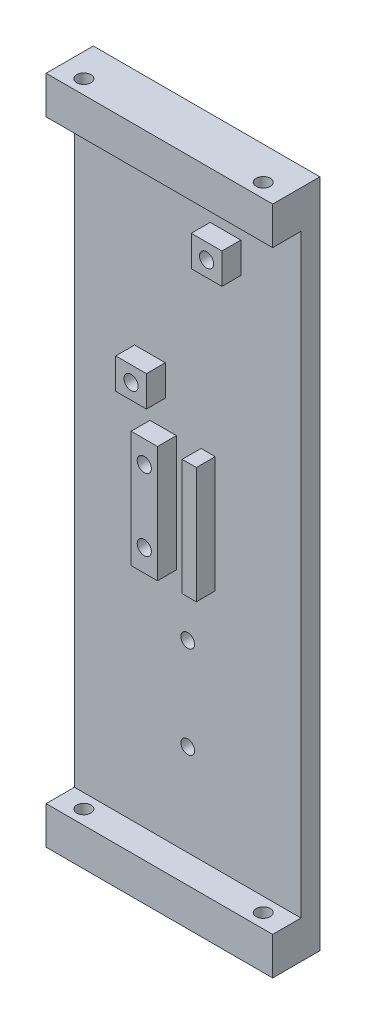
SolidWorks part; units mm, degrees
ref_plane "Płaszczyzna przednia" through (0, 0, 0) normal (0, 0, 1) x (1, 0, 0)
ref_plane "Płaszczyzna górna" through (0, 0, 0) normal (0, 1, 0) x (1, 0, 0)
ref_plane "Płaszczyzna prawa" through (0, 0, 0) normal (1, 0, 0) x (0, 0, -1)
sketch "Szkic1" plane through (0, 0, 0) normal (0, 0, 1) x (1, 0, 0)
  line L0 (-35.2833, 71) -> (12.7167, 71)
  line L5 (-35.2833, -71) -> (12.7167, -71)
  line L6 (-35.2833, -71) -> (-35.2833, 71)
  line L8 (12.7167, -71) -> (12.7167, 71)
  point P4 (0, 0)
  dimension "D1" = 48
  dimension "D2" = 142
extrude "Dodanie-wyciągnięcie1" add sketch "Szkic1" along normal blind 4
sketch "Szkic2" plane through (0, 0, 4) normal (0, 0, 1) x (1, 0, 0)
  line L0 (-16.4833, 8.5426) -> (-16.4833, -8.5426) construction
  line L1 (-16.4833, -8.5426) -> (-16.4833, -12.3226) construction
  line L2 (-16.4833, 8.5426) -> (-16.4833, 12.3176) construction
  line L3 (-13.6833, 12.3176) -> (-19.2833, 12.3176)
  line L4 (-19.2833, 12.3176) -> (-19.2833, -12.3226)
  line L5 (-19.2833, -12.3226) -> (-16.4833, -12.3226)
  line L6 (-16.4833, -12.3226) -> (-13.6833, -12.3226)
  line L7 (-13.6833, -12.3226) -> (-13.6833, 12.3176)
  line L8 (-35.2833, 71) -> (-35.2833, -71) construction
  line L10 (0, 0) -> (-16.4833, 0) construction
  line L11 (-19.2833, -12.3226) -> (-11.2833, -12.3226) construction
  point P9 (-16.4833, 12.3176)
  dimension "D1" = 3.775
  dimension "D2" = 3.78
  dimension "D3" = 5.6
  dimension "D4" = 24
  dimension "D5" = 90
  dimension "D6" = 8
extrude "Dodanie-wyciągnięcie3" add sketch "Szkic2" along normal blind 4
sketch "Szkic3" plane through (0, 0, 8) normal (0, 0, 1) x (1, 0, 0)
  line L0 (-11.2833, -0.0025) -> (-19.2833, -0.0025) construction
  line L1 (-19.2833, -0.0025) -> (-16.4833, -0.0025) construction
  line L2 (-16.4833, -0.0025) -> (-16.4833, 7.6225) construction
  line L3 (-16.4833, -0.0025) -> (-16.4833, -7.6325) construction
  line L4 (-19.2833, 12.3176) -> (-19.2833, -12.3226) construction
  circle A0 centre (-16.4833, 7.6225) radius 1.5
  circle A1 centre (-16.4833, -7.6325) radius 1.5
  dimension "D5" = 3
  dimension "D6" = 3
  dimension "D1" = 8
  dimension "D2" = 2.8
  dimension "D3" = 7.625
  dimension "D4" = 7.63
extrude "Wytnij-wyciągnięcie1" cut sketch "Szkic3" against normal blind 10 and the other way blind 55
sketch "Szkic4" plane through (0, 0, 4) normal (0, 0, 1) x (1, 0, 0)
  line L0 (-6.9633, -12.069) -> (-13.6833, -12.3226) construction
  line L1 (-6.9633, 12.571) -> (-13.6833, 12.3176) construction
  line L2 (-8.4633, 12.571) -> (-5.4633, 12.571)
  line L3 (-8.4633, -12.069) -> (-5.4633, -12.069)
  line L4 (-5.4633, 12.571) -> (-5.4633, -12.069)
  line L5 (-8.4633, -12.069) -> (-8.4633, 12.571)
  line L6 (0, 0) -> (12.7167, 0) construction
  line L7 (12.7167, -71) -> (12.7167, 71) construction
  point P9 (-6.9633, 12.571)
  point P12 (-6.9633, -12.069)
  dimension "D1" = 6.72
  dimension "D2" = 6.72
  dimension "D3" = 3
  dimension "D4" = 3
  dimension "D5" = 24.64
extrude "Dodanie-wyciągnięcie4" add sketch "Szkic4" along normal blind 4
sketch "Szkic5" plane through (0, 0, 4) normal (0, 0, 1) x (1, 0, 0)
  line L0 (-35.2833, 71) -> (-35.2833, 63) construction
  line L1 (-35.2833, 71) -> (-35.2833, -71) construction
  line L2 (-35.2833, 63) -> (12.7167, 63) construction
  line L3 (12.7167, -71) -> (12.7167, 71) construction
  line L4 (12.7167, 63) -> (12.7167, 71) construction
  line L5 (12.7167, 71) -> (-35.2833, 71) construction
  line L6 (-35.2833, 63) -> (12.7167, 63)
  line L7 (12.7167, 63) -> (12.7167, 71)
  line L8 (12.7167, 71) -> (-35.2833, 71)
  line L9 (-35.2833, 71) -> (-35.2833, 63)
  dimension "D1" = 8
extrude "Dodanie-wyciągnięcie5" add sketch "Szkic5" along normal blind 6
sketch "Szkic6" plane through (0, 0, 4) normal (0, 0, 1) x (1, 0, 0)
  line L0 (-35.2833, -71) -> (12.7167, -71)
  line L1 (12.7167, -71) -> (12.7167, -63)
  line L2 (12.7167, -71) -> (12.7167, 63) construction
  line L3 (12.7167, -63) -> (-35.2833, -63)
  line L4 (-35.2833, 63) -> (-35.2833, -71) construction
  line L5 (-35.2833, -63) -> (-35.2833, -71)
  dimension "D1" = 8
extrude "Dodanie-wyciągnięcie6" add sketch "Szkic6" along normal blind 6
sketch "Szkic9" plane through (0, -71, 0) normal (0, -1, 0) x (1, 0, 0)
  line L0 (-35.2833, 10) -> (12.7167, 10) construction
  line L1 (12.7167, 10) -> (12.7167, 0) construction
  line L2 (-35.2833, 10) -> (-35.2833, 0) construction
  circle A0 centre (-30.2833, 7) radius 1.5
  circle A1 centre (7.7167, 7) radius 1.5
  dimension "D3" = 3
  dimension "D4" = 3
  dimension "D1" = 3
  dimension "D2" = 3
  dimension "D5" = 5
  dimension "D6" = 5
extrude "Wytnij-wyciągnięcie4" cut sketch "Szkic9" against normal blind 10
sketch "Szkic10" plane through (0, 71, 0) normal (0, 1, 0) x (-1, 0, 0)
  line L0 (-12.7167, 10) -> (35.2833, 10) construction
  line L1 (-12.7167, 10) -> (-12.7167, 0) construction
  line L2 (35.2833, 10) -> (35.2833, 0) construction
  circle A0 centre (-7.7167, 7) radius 1.5
  circle A1 centre (30.2833, 7) radius 1.5
  dimension "D3" = 3
  dimension "D4" = 3
  dimension "D1" = 3
  dimension "D6" = 5
  dimension "D2" = 5
  dimension "D5" = 3
extrude "Wytnij-wyciągnięcie5" cut sketch "Szkic10" against normal blind 10
sketch "Szkic12" plane through (0, 0, 4) normal (0, 0, 1) x (1, 0, 0)
  line L1 (-19.2833, 21.2635) -> (-19.2833, 51.7635) construction
  line L2 (-19.2833, 51.7635) -> (-3.2833, 51.7635) construction
  line L4 (-22.5333, 24.5135) -> (-16.0333, 24.5135)
  line L5 (-22.5333, 24.5135) -> (-22.5333, 18.0135)
  line L6 (-22.5333, 18.0135) -> (-16.0333, 18.0135)
  line L7 (-16.0333, 24.5135) -> (-16.0333, 18.0135)
  line L8 (-22.5333, 24.5135) -> (-16.0333, 18.0135) construction
  line L9 (-22.5333, 18.0135) -> (-16.0333, 24.5135) construction
  line L10 (-0.0333, 55.0135) -> (-6.5333, 55.0135)
  line L11 (-0.0333, 55.0135) -> (-0.0333, 48.5135)
  line L12 (-0.0333, 48.5135) -> (-6.5333, 48.5135)
  line L13 (-6.5333, 55.0135) -> (-6.5333, 48.5135)
  line L14 (-0.0333, 55.0135) -> (-6.5333, 48.5135) construction
  line L15 (-0.0333, 48.5135) -> (-6.5333, 55.0135) construction
  line L16 (-35.2833, 63) -> (-35.2833, -63) construction
  circle A0 centre (-19.2833, 21.2635) radius 1.5
  circle A1 centre (-3.2833, 51.7635) radius 1.5
  dimension "D4" = 3
  dimension "D5" = 3
  dimension "D1" = 12.75
  dimension "D2" = 30.5
  dimension "D3" = 16
  dimension "D6" = 6.5
  dimension "D7" = 6.5
  dimension "D8" = 6.5
  dimension "D9" = 6.5
extrude "Dodanie-wyciągnięcie7" add sketch "Szkic12" along normal blind 4
sketch "Szkic15" plane through (0, 0, 4) normal (0, 0, 1) x (1, 0, 0)
  line L0 (-35.2833, -24.0673) -> (-11.2833, -24.0673) construction
  line L1 (-35.2833, 63) -> (-35.2833, -63) construction
  line L2 (-11.2833, -24.0673) -> (-11.2833, -12.0673) construction
  line L3 (-11.2833, -24.0673) -> (-21.0333, -24.0673) construction
  line L4 (-11.2833, -24.0673) -> (-11.2833, -43.5673) construction
  circle A2 centre (-11.2833, -24.0673) radius 1.45
  circle A3 centre (-11.2833, -43.5673) radius 1.45
  dimension "D5" = 2.9
  dimension "D4" = 2.9
  dimension "D1" = 24
  dimension "D2" = 12
  dimension "D3" = 19.5
extrude "Wytnij-wyciągnięcie6" cut sketch "Szkic15" against normal blind 10
sketch "Szkic16" plane through (0, 0, 8) normal (0, 0, 1) x (1, 0, 0)
  circle A0 centre (-3.2833, 51.7635) radius 1.5
  circle A1 centre (-19.2833, 21.2635) radius 1.5
extrude "Wytnij-wyciągnięcie7" cut sketch "Szkic16" against normal blind 10
chamfer "Sfazowanie1" distance 1 angle 45 4 edges at (-4.7833, 51.7635, 0) (-20.7833, 21.2635, 0) (-17.9833, 7.6225, 0) (-17.9833, -7.6325, 0)
